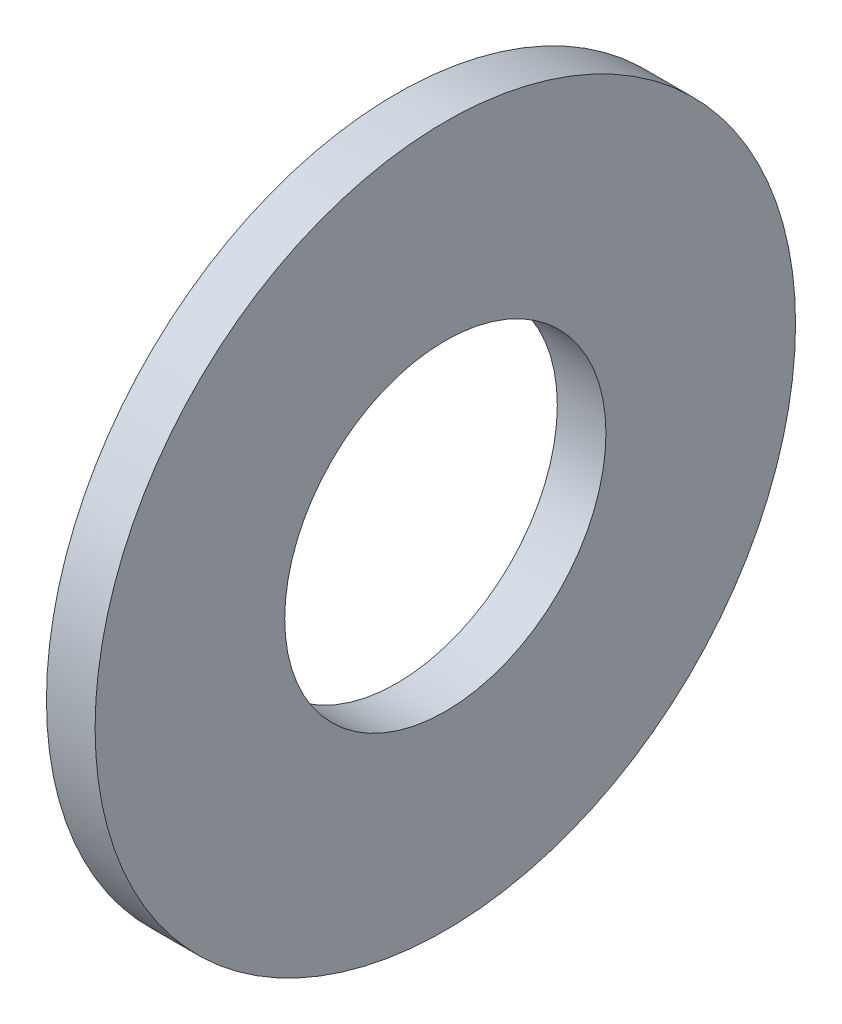
SolidWorks part; units mm, degrees
ref_plane "Plane1" through (0, 0, 0) normal (0, 0, 1) x (1, 0, 0)
ref_plane "Plane2" through (0, 0, 0) normal (0, 1, 0) x (1, 0, 0)
ref_plane "Plane3" through (0, 0, 0) normal (1, 0, 0) x (0, 0, -1)
other "Configuration Table"
sketch "Sketch1" plane through (0, 0, 0) normal (0, 0, 1) x (1, 0, 0)
  line L0 (-34.925, 0) -> (9.525, 0) construction
  line L1 (0, 16.51) -> (0, 36)
  line L2 (0, 36) -> (-5, 36)
  line L3 (-5, 36) -> (-5, 16.51)
  line L4 (-5, 16.51) -> (0, 16.51)
  dimension "Thickness" = 5
  dimension "Inside_dia" = 33.02
  dimension "Outside_dia" = 72
revolve "Base-Revolve" add sketch "Sketch1" angle 360 about L0
